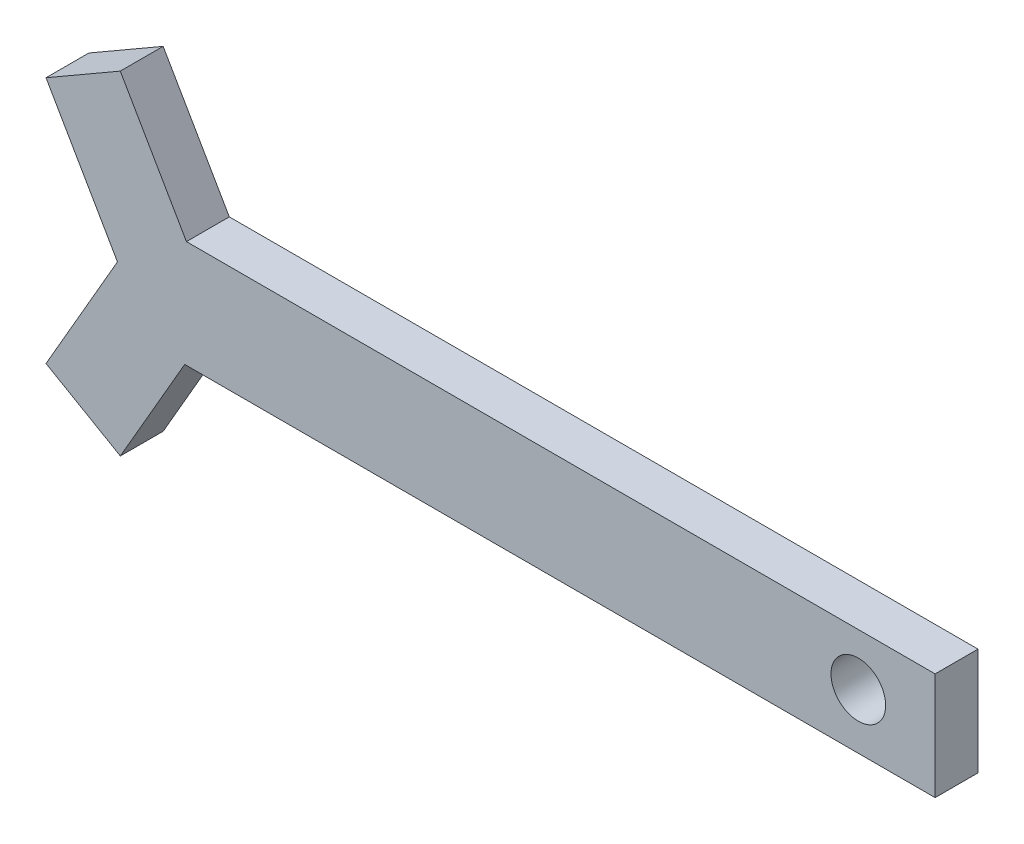
SolidWorks part; units mm, degrees
ref_plane "Plano frontal" through (0, 0, 0) normal (0, 0, 1) x (1, 0, 0)
ref_plane "Plano superior" through (0, 0, 0) normal (0, 1, 0) x (1, 0, 0)
ref_plane "Plano direito" through (0, 0, 0) normal (1, 0, 0) x (0, 0, -1)
sketch "Esboço1" plane through (0, 0, 0) normal (0, 0, 1) x (1, 0, 0)
  line L0 (52.7042, -2.4005) -> (-17.1362, -2.4005)
  line L1 (-17.1362, -2.4005) -> (-23.3076, 8.2889)
  line L2 (-23.3076, 8.2889) -> (-30.2358, 4.2889)
  line L3 (-30.2358, 4.2889) -> (-23.5708, -7.2554)
  line L4 (-23.5708, -7.2554) -> (-30.2358, -18.7996)
  line L5 (-30.2358, -18.7996) -> (-23.3017, -22.803)
  line L6 (-23.3017, -22.803) -> (-17.2958, -12.4005)
  line L7 (-17.2958, -12.4005) -> (52.7042, -12.4005)
  line L8 (52.7042, -12.4005) -> (52.7042, -2.4005)
  circle A0 centre (45.5388, -7.2554) radius 2.55
  dimension "D1" = 5.1
  dimension "D2" = 10
  dimension "D3" = 120
extrude "Ressalto-extrusão1" add sketch "Esboço1" along normal blind 4
